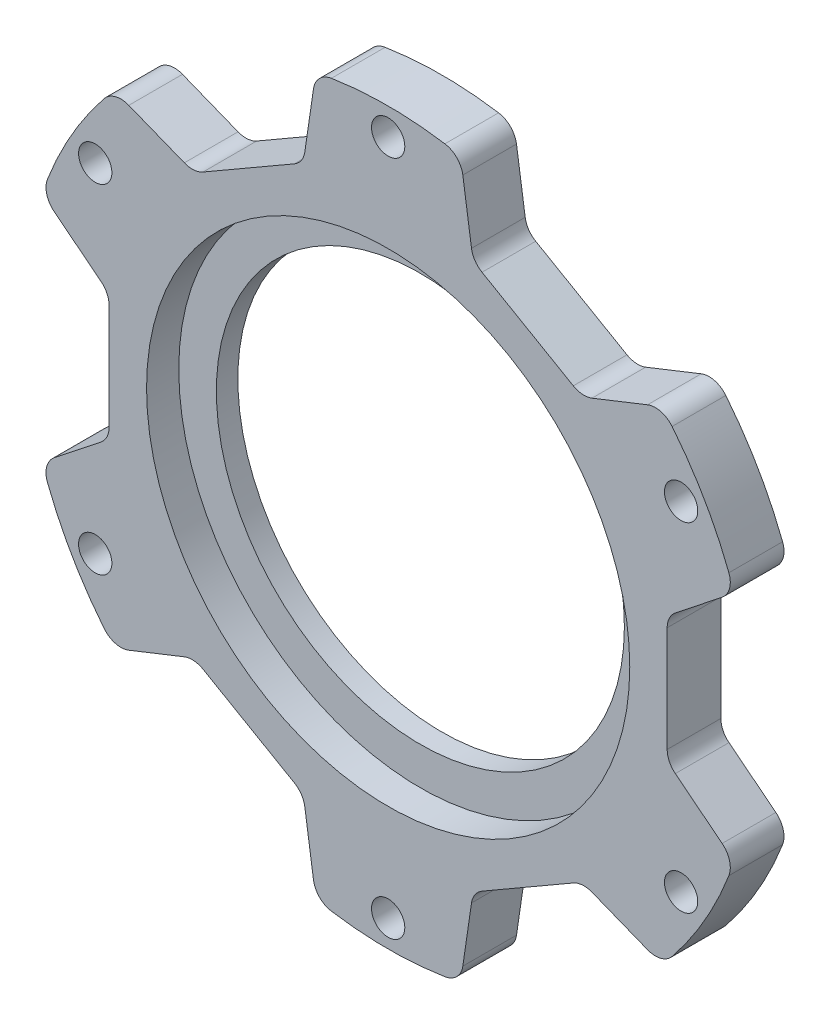
SolidWorks part; units mm, degrees
ref_plane "前视基准面" through (0, 0, 0) normal (0, 0, 1) x (1, 0, 0)
ref_plane "上视基准面" through (0, 0, 0) normal (0, 1, 0) x (1, 0, 0)
ref_plane "右视基准面" through (0, 0, 0) normal (1, 0, 0) x (0, 0, -1)
sketch "草图1" plane through (0, 0, 0) normal (0, 0, 1) x (1, 0, 0)
  circle A0 centre (0, 0) radius 34
  circle A1 centre (0, 0) radius 19
  dimension "D1" = 68
  dimension "D2" = 38
extrude "凸台-拉伸1" add sketch "草图1" along normal blind 5
sketch "草图2" plane through (0, 0, 5) normal (0, 0, 1) x (1, 0, 0)
  circle A0 centre (0, 0) radius 22.5
  dimension "D1" = 45
extrude "切除-拉伸1" cut sketch "草图2" against normal blind 3
sketch "草图3" plane through (0, 0, 0) normal (0, 0, -1) x (-1, 0, 0)
  circle A0 centre (0, 0) radius 31.5 construction
  circle A1 centre (0, 31.5) radius 1.55
  circle A2 centre (27.2798, 15.75) radius 1.55
  circle A3 centre (27.2798, -15.75) radius 1.55
  circle A4 centre (0, -31.5) radius 1.55
  circle A5 centre (-27.2798, -15.75) radius 1.55
  circle A6 centre (-27.2798, 15.75) radius 1.55
  point P17 (0, 0)
  dimension "D1" = 63
  dimension "D2" = 3.1
  dimension "D3" = 6
extrude "切除-拉伸2" cut sketch "草图3" against normal blind 13
sketch "草图4" plane through (0, 0, 0) normal (0, 0, -1) x (-1, 0, 0)
  line L0 (-6.7438, 33.3245) -> (-7.9032, 25.4404)
  line L1 (-27.2798, 15.75) -> (0, 31.5) construction
  line L2 (-7.9032, 25.4404) -> (-18.0805, 19.5646)
  line L3 (-12.9918, 22.5025) -> (-17, 29.4449) construction
  line L4 (-25.488, 22.5025) -> (-18.0805, 19.5646)
  line L5 (6.7438, 33.3245) -> (7.9032, 25.4404)
  line L6 (18.0805, 19.5646) -> (7.9032, 25.4404)
  line L7 (25.488, 22.5025) -> (18.0805, 19.5646)
  line L8 (32.2317, 10.822) -> (25.9837, 5.8758)
  line L9 (25.9837, -5.8758) -> (25.9837, 5.8758)
  line L10 (32.2317, -10.822) -> (25.9837, -5.8758)
  line L11 (25.488, -22.5025) -> (18.0805, -19.5646)
  line L12 (7.9032, -25.4404) -> (18.0805, -19.5646)
  line L13 (6.7438, -33.3245) -> (7.9032, -25.4404)
  line L14 (-6.7438, -33.3245) -> (-7.9032, -25.4404)
  line L15 (-18.0805, -19.5646) -> (-7.9032, -25.4404)
  line L16 (-25.488, -22.5025) -> (-18.0805, -19.5646)
  line L17 (-32.2317, -10.822) -> (-25.9837, -5.8758)
  line L18 (-25.9837, 5.8758) -> (-25.9837, -5.8758)
  line L19 (-32.2317, 10.822) -> (-25.9837, 5.8758)
  arc A0 (-6.7438, 33.3245) -> (-25.488, 22.5025) centre (0, 0) ccw
  circle A1 centre (0, 0) radius 34 construction
  arc A2 (25.488, 22.5025) -> (6.7438, 33.3245) centre (0, 0) ccw
  arc A3 (32.2317, -10.822) -> (32.2317, 10.822) centre (0, 0) ccw
  arc A4 (6.7438, -33.3245) -> (25.488, -22.5025) centre (0, 0) ccw
  arc A5 (-25.488, -22.5025) -> (-6.7438, -33.3245) centre (0, 0) ccw
  arc A6 (-32.2317, 10.822) -> (-32.2317, -10.822) centre (0, 0) ccw
  point P36 (0, 0)
  dimension "D1" = 6
extrude "切除-拉伸3" cut sketch "草图4" against normal blind 13
fillet "圆角1" radius 2 24 edges at (25.9837, -5.8758, 2.5) (25.9837, 5.8758, 2.5) (7.9032, -25.4404, 2.5) (18.0805, -19.5646, 2.5) (-18.0805, -19.5646, 2.5) (-7.9032, -25.4404, 2.5) (-25.9837, -5.8758, 2.5) (-25.9837, 5.8758, 2.5) (-7.9032, 25.4404, 2.5) (-18.0805, 19.5646, 2.5) (7.9032, 25.4404, 2.5) (18.0805, 19.5646, 2.5) (25.488, 22.5025, 2.5) (32.2317, 10.822, 2.5) (32.2317, -10.822, 2.5) (25.488, -22.5025, 2.5) (6.7438, -33.3245, 2.5) (-6.7438, -33.3245, 2.5) (-25.488, -22.5025, 2.5) (-32.2317, -10.822, 2.5) (-32.2317, 10.822, 2.5) (-25.488, 22.5025, 2.5) (-6.7438, 33.3245, 2.5) (6.7438, 33.3245, 2.5)
